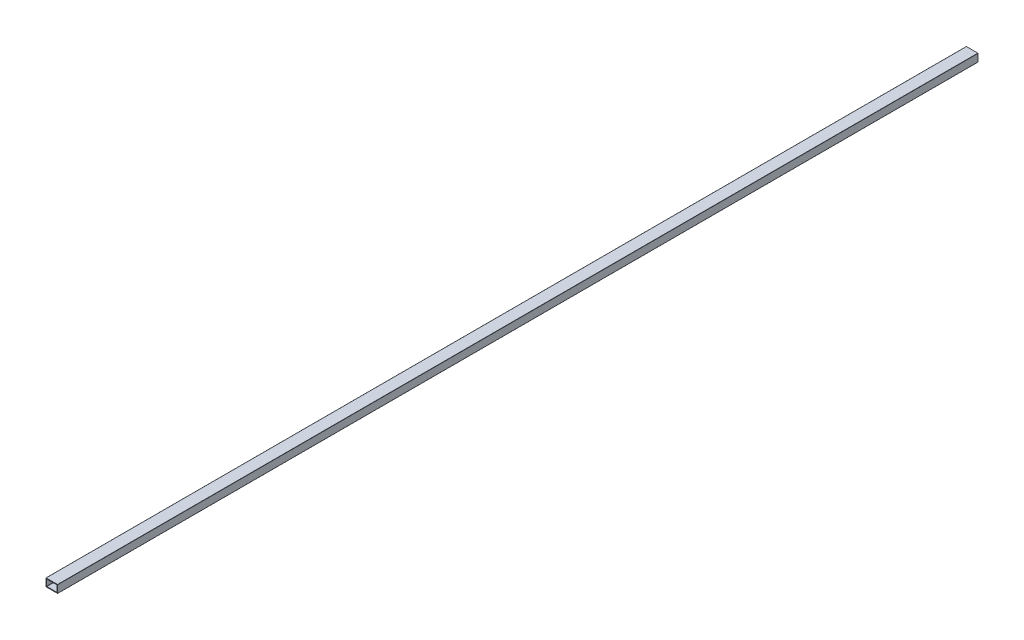
SolidWorks part; units mm, degrees
material "AISI 1035 Acero (SS)"
ref_plane "Alzado" through (0, 0, 0) normal (0, 0, 1) x (1, 0, 0)
ref_plane "Planta" through (0, 0, 0) normal (0, 1, 0) x (1, 0, 0)
ref_plane "Vista lateral" through (0, 0, 0) normal (1, 0, 0) x (0, 0, -1)
sketch "Croquis1" plane through (0, 0, 0) normal (0, 0, 1) x (1, 0, 0)
  line L0 (-33.55, -20.85) -> (-33.55, 20.85)
  line L1 (-38.1, -25.4) -> (38.1, -25.4)
  line L2 (-38.1, -25.4) -> (-38.1, 25.4)
  line L3 (-38.1, 25.4) -> (38.1, 25.4)
  line L4 (38.1, -25.4) -> (38.1, 25.4)
  line L5 (-38.1, -25.4) -> (38.1, 25.4) construction
  line L6 (-38.1, 25.4) -> (38.1, -25.4) construction
  line L7 (-33.55, 20.85) -> (33.55, 20.85)
  line L8 (33.55, -20.85) -> (33.55, 20.85)
  line L9 (-33.55, -20.85) -> (33.55, -20.85)
  point P0 (0, 0)
  dimension "D1" = 50.8
  dimension "D2" = 76.2
  dimension "D3" = 4.55
extrude "Saliente-Extruir1" add sketch "Croquis1" against normal blind 6000
fillet "Redondeo1" radius 1 8 edges at (-33.55, 20.85, -3000) (33.55, 20.85, -3000) (33.55, -20.85, -3000) (-38.1, -25.4, -3000) (-38.1, 25.4, -3000) (-33.55, -20.85, -3000) (38.1, -25.4, -3000) (38.1, 25.4, -3000)
